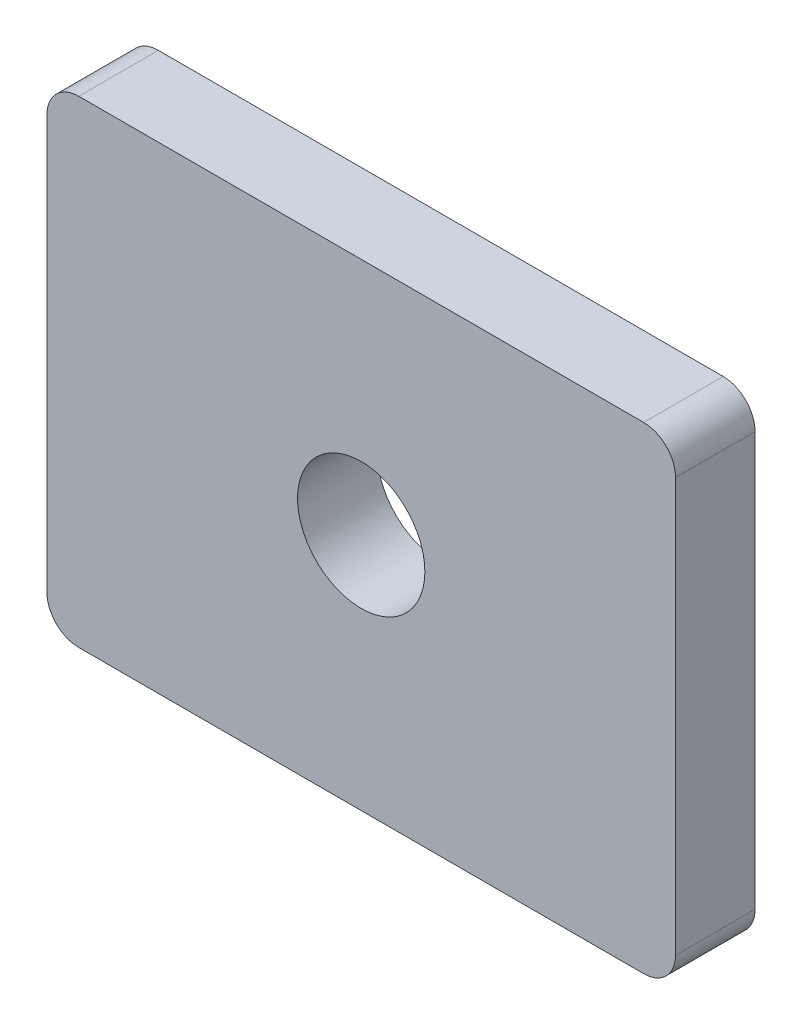
SolidWorks part; units mm, degrees
ref_plane "Front Plane" through (0, 0, 0) normal (0, 0, 1) x (1, 0, 0)
ref_plane "Top Plane" through (0, 0, 0) normal (0, 1, 0) x (1, 0, 0)
ref_plane "Right Plane" through (0, 0, 0) normal (1, 0, 0) x (0, 0, -1)
sketch "Sketch1" plane through (0, 0, 0) normal (0, 0, 1) x (1, 0, 0)
  line L1 (-19.75, 15) -> (19.75, 15)
  line L2 (-19.75, 15) -> (-19.75, -15)
  line L3 (-19.75, -15) -> (19.75, -15)
  line L4 (19.75, 15) -> (19.75, -15)
  line L5 (-19.75, 15) -> (19.75, -15) construction
  line L6 (-19.75, -15) -> (19.75, 15) construction
  circle A0 centre (0, 0) radius 4
  point P0 (0, 0)
  dimension "D3" = 8
  dimension "D1" = 39.5
  dimension "D2" = 30
extrude "Boss-Extrude1" add sketch "Sketch1" along normal blind 5
fillet "Fillet1" radius 2 4 edges at (-19.75, -15, 2.5) (19.75, -15, 2.5) (-19.75, 15, 2.5) (19.75, 15, 2.5)
